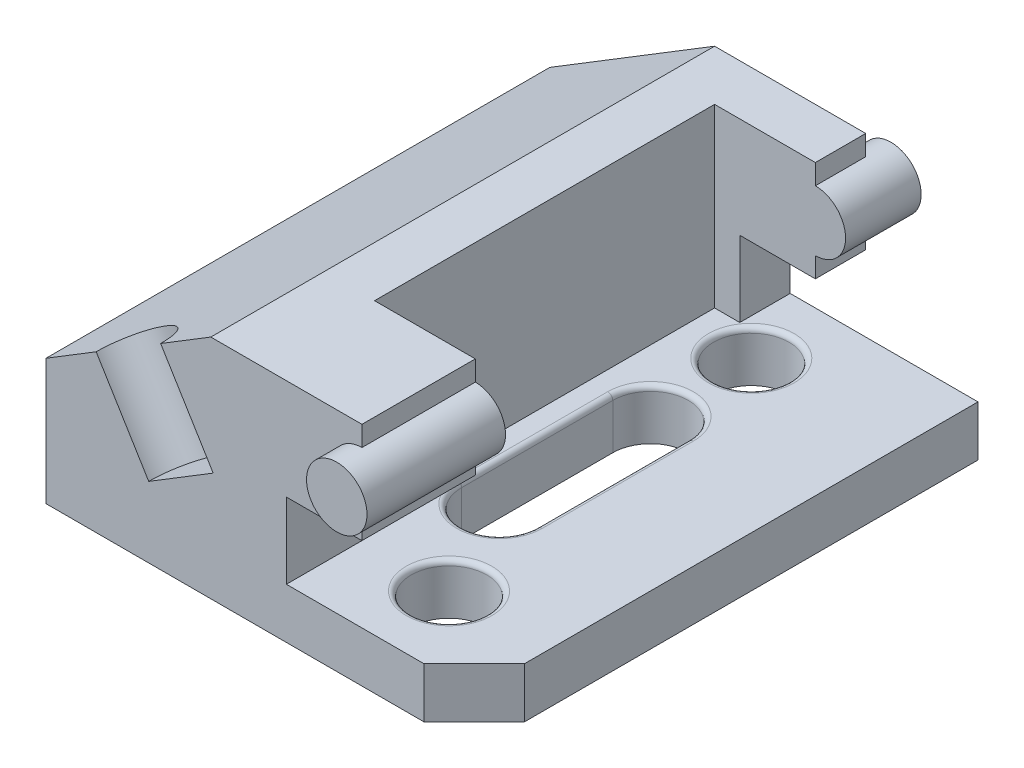
SolidWorks part; units mm, degrees
material "1060 Alloy"
ref_plane "Front Plane" through (0, 0, 0) normal (0, 0, 1) x (1, 0, 0)
ref_plane "Top Plane" through (0, 0, 0) normal (0, 1, 0) x (1, 0, 0)
ref_plane "Right Plane" through (0, 0, 0) normal (1, 0, 0) x (0, 0, -1)
sketch "Sketch1" plane through (0, 0, 0) normal (0, 0, 1) x (1, 0, 0)
  line L0 (0, 0) -> (85, 0)
  line L1 (85, 10) -> (47.7151, 10)
  line L2 (47.7151, 10) -> (47.7151, 25)
  line L3 (47.7151, 25) -> (62.7151, 25)
  line L4 (62.7151, 45) -> (62.7151, 25)
  line L5 (85, 10) -> (85, 0)
  line L6 (0, 0) -> (0, 25)
  line L7 (0, 25) -> (32.7151, 45)
  line L8 (32.7151, 45) -> (62.7151, 45)
  dimension "D1" = 85
  dimension "D2" = 25
  dimension "D3" = 30
  dimension "D4" = 20
  dimension "D5" = 15
  dimension "D6" = 15
  dimension "D7" = 10
extrude "Boss-Extrude1" add sketch "Sketch1" against normal blind 100
sketch "Sketch2" plane through (0, 10, 0) normal (0, 1, 0) x (1, 0, 0)
  line L0 (47.5, 65) -> (47.5, 35)
  line L1 (62.5, 65) -> (62.5, 35)
  line L2 (85, 100) -> (47.7151, 100) construction
  line L3 (85, 0) -> (47.7151, 0) construction
  line L4 (85, 100) -> (85, 0) construction
  circle A0 centre (55, 85) radius 7.5
  circle A1 centre (65, 15) radius 7.5
  arc A2 (47.5, 65) -> (62.5, 65) centre (55, 65) cw
  arc A3 (47.5, 35) -> (62.5, 35) centre (55, 35) ccw
  point P14 (0, 0)
  point P15 (0, 0)
  point P20 (64.5132, 33.5232)
  dimension "D7" = 15
  dimension "D1" = 15
  dimension "D2" = 15
  dimension "D3" = 15
  dimension "D4" = 20
  dimension "D5" = 20
  dimension "D6" = 30
extrude "Cut-Extrude2" cut sketch "Sketch2" against normal blind 100 contours A3 L1 A2 L0 | A1
sketch "Sketch3" plane through (0, 10, 0) normal (0, 1, 0) x (1, 0, 0)
  line L0 (85, 100) -> (47.7151, 100) construction
  line L1 (85, 100) -> (85, 0) construction
  circle A0 centre (55, 85) radius 7.5
  dimension "D2" = 15
  dimension "D1" = 15
  dimension "D3" = 30
extrude "Cut-Extrude3" cut sketch "Sketch3" against normal blind 100
sketch "Sketch4" plane through (0, 10, 0) normal (0, 1, 0) x (1, 0, 0)
  line L0 (75, 0) -> (85, 10)
  line L1 (85, 0) -> (47.7151, 0) construction
  line L2 (85, 100) -> (85, 0) construction
  line L3 (85, 10) -> (85, 0)
  line L4 (85, 0) -> (75, 0)
  dimension "D1" = 10
  dimension "D2" = 45
extrude "Cut-Extrude4" cut sketch "Sketch4" against normal blind 100
sketch "Sketch5" plane through (-11.1255, 18.1986, 0) normal (-0.5216, 0.8532, 0) x (0.8532, 0.5216, 0)
  line L0 (51.384, 0) -> (13.0398, 0) construction
  circle A0 centre (32.2119, 0) radius 7.5
  dimension "D1" = 15
extrude "Cut-Extrude5" cut sketch "Sketch5" against normal blind 20
sketch "Sketch7" plane through (0, 0, 0) normal (0, 0, 1) x (1, 0, 0)
  line L0 (62.7151, 25) -> (62.7151, 45) construction
  circle A0 centre (62.7151, 35) radius 6
  dimension "D1" = 12
extrude "Boss-Extrude2" add sketch "Sketch7" against normal blind 105 and the other way blind 5
sketch "Sketch8" plane through (0, 45, 0) normal (0, 1, 0) x (1, 0, 0)
  line L0 (62.7151, 90) -> (42.7151, 90)
  line L1 (62.7151, 100) -> (62.7151, 0) construction
  line L2 (42.7151, 90) -> (42.7151, 22.5)
  line L3 (42.7151, 22.5) -> (72.7151, 22.5)
  line L4 (72.7151, 22.5) -> (72.7151, 90)
  line L5 (72.7151, 90) -> (62.7151, 90)
  line L6 (62.7151, 100) -> (32.7151, 100) construction
  line L7 (32.7151, 100) -> (32.7151, 0) construction
  dimension "D1" = 10
  dimension "D2" = 67.5
  dimension "D3" = 10
  dimension "D4" = 30
extrude "Cut-Extrude6" cut sketch "Sketch8" against normal up to surface (35 mm away)
fillet "Fillet1" radius 1 6 edges at (55, 10, -72.5) (62.5, 10, -50) (55, 10, -27.5) (47.5, 10, -85) (47.5, 10, -50) (57.5, 10, -15)
